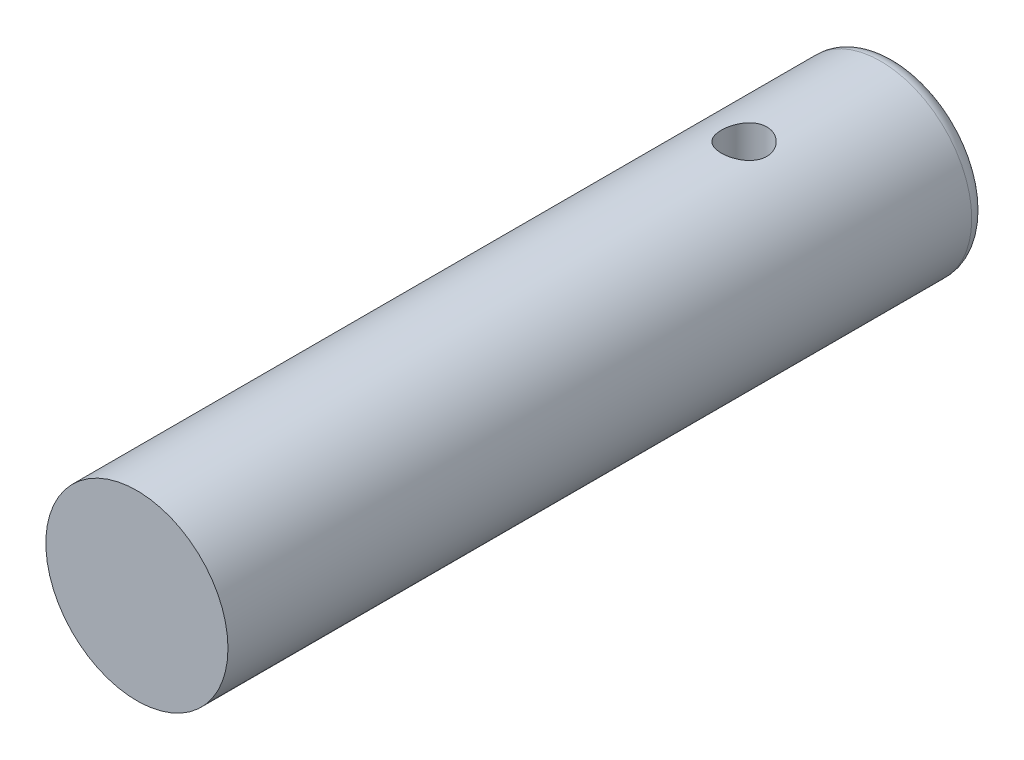
SolidWorks part; units mm, degrees
ref_plane "Front Plane" through (0, 0, 0) normal (0, 0, 1) x (1, 0, 0)
ref_plane "Top Plane" through (0, 0, 0) normal (0, 1, 0) x (1, 0, 0)
ref_plane "Right Plane" through (0, 0, 0) normal (1, 0, 0) x (0, 0, -1)
sketch "Sketch2" plane through (0, 0, 0) normal (0, 0, 1) x (1, 0, 0)
  circle A0 centre (0, 0) radius 3
  dimension "D1" = 6
extrude "Boss-Extrude1" add sketch "Sketch2" along normal blind 25
sketch "Sketch3" plane through (0, 0, 0) normal (0, 1, 0) x (1, 0, 0)
  line L0 (0, 3.6803) -> (0, -26.6314) construction
  line L1 (3, 0) -> (-3, 0) construction
  circle A0 centre (0, -5) radius 0.75
  dimension "D1" = 1.5
  dimension "D2" = 5
extrude "Cut-Extrude1" cut sketch "Sketch3" against normal through all both and the other way through all
fillet "Fillet1" radius 0.5 1 edges at (3, 0, 0)
